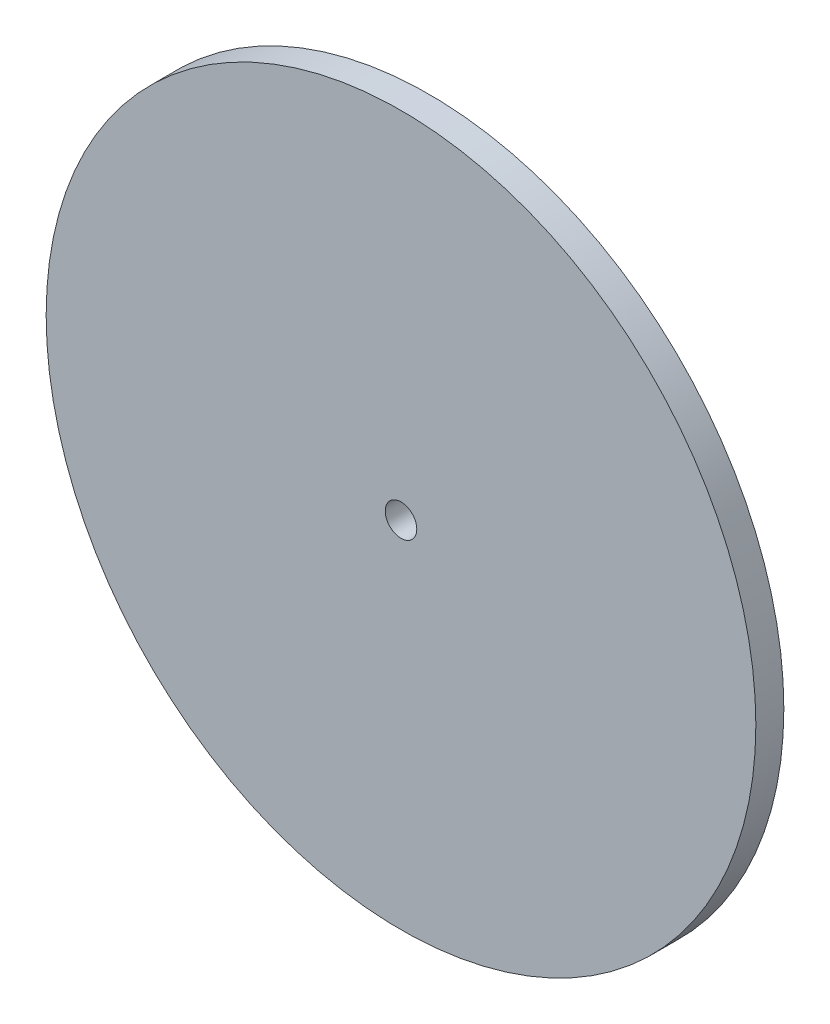
SolidWorks part; units mm, degrees
ref_plane "Front Plane" through (0, 0, 0) normal (0, 0, 1) x (1, 0, 0)
ref_plane "Top Plane" through (0, 0, 0) normal (0, 1, 0) x (1, 0, 0)
ref_plane "Right Plane" through (0, 0, 0) normal (1, 0, 0) x (0, 0, -1)
sketch "Sketch1" plane through (0, 0, 0) normal (0, 0, 1) x (1, 0, 0)
  circle A0 centre (0, 0) radius 45
  dimension "D1" = 90
extrude "Boss-Extrude1" add sketch "Sketch1" along normal blind 3.55 contours A0
sketch "Sketch2" plane through (0, 0, 3.55) normal (0, 0, 1) x (1, 0, 0)
  circle A0 centre (0, 0) radius 2
  dimension "D1" = 4
  dimension "D2" = 4
extrude "Cut-Extrude1" cut sketch "Sketch2" against normal blind 4
